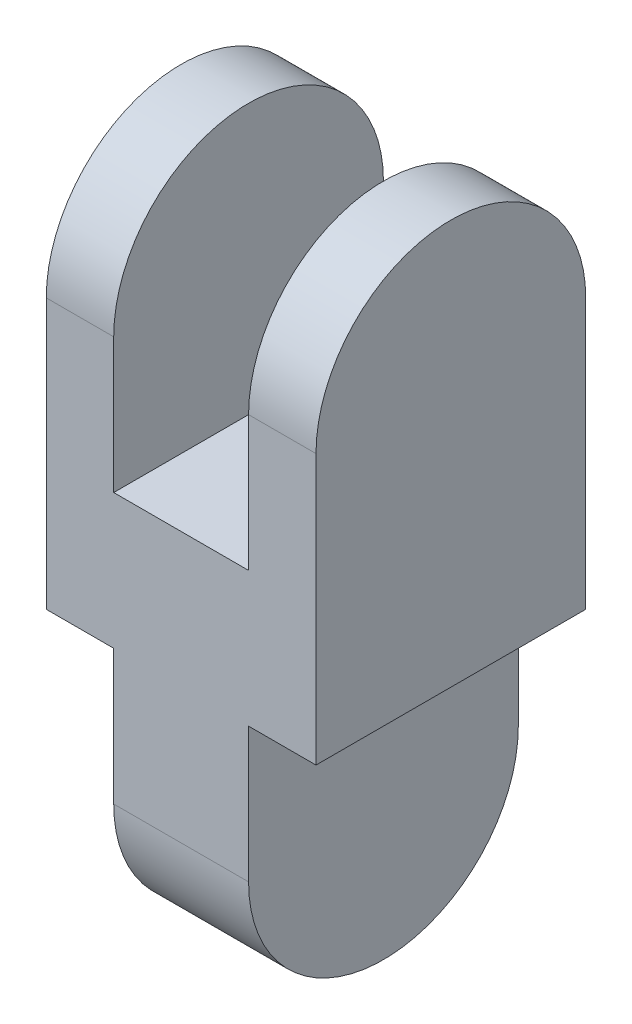
SolidWorks part; units mm, degrees
ref_plane "Front" through (0, 0, 0) normal (0, 0, 1) x (1, 0, 0)
ref_plane "Top" through (0, 0, 0) normal (0, 1, 0) x (1, 0, 0)
ref_plane "Right" through (0, 0, 0) normal (1, 0, 0) x (0, 0, -1)
sketch "草图1" plane through (0, 0, 0) normal (0, 1, 0) x (1, 0, 0)
  line L0 (-18.2439, 0) -> (0, 0) construction
  line L1 (0, 0) -> (0, 18.5122) construction
  line L3 (-8, 8) -> (8, 8)
  line L4 (-8, 8) -> (-8, -8)
  line L5 (-8, -8) -> (8, -8)
  line L6 (8, 8) -> (8, -8)
  dimension "D1" = 16
  dimension "D2" = 16
  dimension "D3" = 8
  dimension "D4" = 8
extrude "凸台-拉伸1" add sketch "草图1" along normal blind 40
sketch "草图2" plane through (8, 0, 0) normal (1, 0, 0) x (0, 0, -1)
  line L0 (0, 0) -> (0, 40) construction
  line L1 (-8, 40) -> (8, 40) construction
  line L4 (-8, 8) -> (-8, -6.7486)
  line L5 (-8, -6.7486) -> (8, -6.7486)
  line L6 (8, 8) -> (8, -6.7486)
  arc A0 (-8, 8) -> (8, 8) centre (0, 8) ccw
extrude "切除-拉伸1" cut sketch "草图2" against normal blind 40
sketch "草图4" plane through (-8, 0, 0) normal (-1, 0, 0) x (0, 0, 1)
  line L0 (8, 40) -> (8, 8) construction
  line L2 (-8, 8) -> (-8, 16)
  line L3 (-8, 16) -> (8, 16)
  line L4 (8, 8) -> (8, 16)
  arc A0 (-8, 8) -> (8, 8) centre (0, 8) ccw
extrude "切除-拉伸2" cut sketch "草图4" against normal blind 4
sketch "草图5" plane through (8, 0, 0) normal (1, 0, 0) x (0, 0, -1)
  line L0 (0, 0) -> (0, 40) construction
  line L1 (-8, 40) -> (8, 40) construction
  line L4 (-8, 8) -> (-8, 16)
  line L5 (-8, 16) -> (8, 16)
  line L6 (8, 8) -> (8, 16)
  arc A0 (-8, 8) -> (8, 8) centre (0, 8) ccw
extrude "切除-拉伸3" cut sketch "草图5" against normal blind 4
sketch "草图7" plane through (0, 0, 0) normal (1, 0, 0) x (0, 0, -1)
  line L0 (0, 40) -> (0, 0) construction
  line L1 (-8, 40) -> (8, 40) construction
  line L2 (8, 40) -> (8, 16) construction
  line L4 (-8, 32) -> (-8, 24)
  line L5 (-8, 24) -> (8, 24)
  line L6 (8, 32) -> (8, 24)
  arc A0 (8, 32) -> (-8, 32) centre (0, 32) ccw
sketch "草图8" plane through (8, 0, 0) normal (1, 0, 0) x (0, 0, -1)
  line L2 (-8, 32) -> (-8, 44.0903)
  line L3 (-8, 44.0903) -> (8, 44.0903)
  line L4 (8, 32) -> (8, 44.0903)
  arc A0 (8, 32) -> (-8, 32) centre (0, 32) ccw
extrude "切除-拉伸7" cut sketch "草图8" against normal through all
extrude "切除-拉伸8" cut sketch "草图7" against normal mid plane 8
